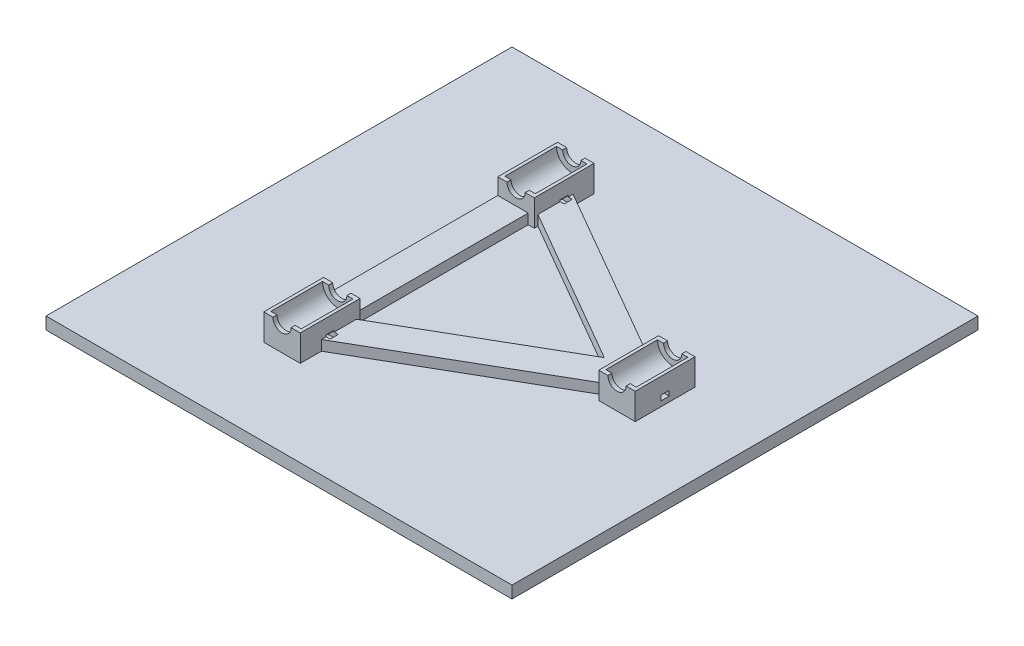
SolidWorks part; units mm, degrees
ref_plane "Front Plane" through (0, 0, 0) normal (0, 0, 1) x (1, 0, 0)
ref_plane "Top Plane" through (0, 0, 0) normal (0, 1, 0) x (1, 0, 0)
ref_plane "Right Plane" through (0, 0, 0) normal (1, 0, 0) x (0, 0, -1)
sketch "bottom" plane through (0, 0, 0) normal (0, 1, 0) x (1, 0, 0)
  line L0 (-133.0584, -12.7792) -> (96.9416, -12.7792) construction
  line L1 (-133.0584, 102.2208) -> (96.9416, 102.2208)
  line L2 (-133.0584, 102.2208) -> (-133.0584, -127.7792)
  line L3 (-133.0584, -127.7792) -> (96.9416, -127.7792)
  line L4 (96.9416, 102.2208) -> (96.9416, -127.7792)
  line L5 (-18.0584, 102.2208) -> (-18.0584, -127.7792) construction
  dimension "D1" = 230
  dimension "D2" = 230
extrude "Boss-Extrude2" add sketch "bottom" along normal blind 6
sketch "Sketch4" plane through (0, 6, 0) normal (0, 1, 0) x (1, 0, 0)
  line L0 (-133.0584, -12.7792) -> (96.9416, -12.7792) construction
  line L1 (-133.0584, 102.2208) -> (-133.0584, -127.7792) construction
  line L2 (96.9416, -127.7792) -> (96.9416, 102.2208) construction
  line L3 (-68.0584, 59.7208) -> (-68.0584, -85.2792)
  line L4 (96.9416, 102.2208) -> (-133.0584, 102.2208) construction
  line L5 (-18.0584, 102.2208) -> (-18.0584, -127.7792) construction
  line L6 (-133.0584, -127.7792) -> (96.9416, -127.7792) construction
  line L7 (-68.0584, -85.2792) -> (57.5153, -12.7792)
  line L8 (57.5153, -12.7792) -> (-68.0584, 59.7208)
  line L9 (-68.0584, -12.7792) -> (57.5153, -12.7792) construction
  line L10 (-53.0584, -59.2984) -> (-53.0584, 33.7401)
  line L11 (-53.0584, 33.7401) -> (27.5153, -12.7792)
  line L12 (57.5153, -12.7792) -> (-68.0584, -12.7792) construction
  line L13 (27.5153, -12.7792) -> (-53.0584, -59.2984)
  dimension "D1" = 145
  dimension "D2" = 145
  dimension "D3" = 50
  dimension "D4" = 15
  dimension "D5" = 15
extrude "Triangle" add sketch "Sketch4" along normal blind 5
sketch "Sketch5" plane through (0, 11, 0) normal (0, 1, 0) x (1, 0, 0)
  line L0 (39.5153, -12.7792) -> (57.5153, -12.7792) construction
  line L1 (-68.0584, 59.7208) -> (-50.0584, 59.7208)
  line L2 (-68.0584, 59.7208) -> (-68.0584, 30.2208)
  line L3 (-68.0584, 30.2208) -> (-50.0584, 30.2208)
  line L4 (-50.0584, 59.7208) -> (-50.0584, 30.2208)
  line L5 (-68.0584, -85.2792) -> (-50.0584, -85.2792)
  line L6 (-68.0584, -85.2792) -> (-68.0584, -55.7792)
  line L7 (-68.0584, -55.7792) -> (-50.0584, -55.7792)
  line L8 (-50.0584, -85.2792) -> (-50.0584, -55.7792)
  line L9 (39.5153, 1.9708) -> (57.5153, 1.9708)
  line L10 (39.5153, 1.9708) -> (39.5153, -27.5292)
  line L11 (39.5153, -27.5292) -> (57.5153, -27.5292)
  line L12 (57.5153, 1.9708) -> (57.5153, -27.5292)
  line L14 (48.5153, 1.9708) -> (48.5153, -27.5292) construction
  dimension "D1" = 29.5
  dimension "D2" = 18
extrude "Boss-Extrude4" add sketch "Sketch5" along normal blind 8 and the other way blind 6
sketch "Sketch6" plane through (0, 0, -30.2208) normal (0, 0, 1) x (1, 0, 0)
  line L0 (-68.0584, 19) -> (-50.0584, 19) construction
  circle A0 centre (-59.0584, 19) radius 4.5
  dimension "D1" = 9
extrude "Rod cutout" cut sketch "Sketch6" against normal up to surface and the other way up to surface up to face at (-59.0584, 12.5, -59.7208) other way up to face at (-59.0584, 12.5, 85.2792)
sketch "Sketch7" plane through (0, 0, -30.2208) normal (0, 0, 1) x (1, 0, 0)
  circle A0 centre (-59.0584, 19) radius 7.5
  dimension "D1" = 15
extrude "LM8Socket 1" cut sketch "Sketch7" against normal blind 25.5 from offset 2 offset against normal yes
sketch "Sketch8" plane through (0, 0, 55.7792) normal (0, 0, -1) x (-1, 0, 0)
  circle A0 centre (59.0584, 19) radius 7.5
  dimension "D1" = 15
extrude "LM8Socket 2" cut sketch "Sketch8" against normal blind 25.5 from offset 2 offset against normal yes
sketch "Sketch9" plane through (0, 0, -1.9708) normal (0, 0, -1) x (-1, 0, 0)
  line L0 (-57.5153, 19) -> (-39.5153, 19) construction
  circle A0 centre (-48.5153, 19) radius 4.5
  dimension "D1" = 9
extrude "Cut-Extrude4" cut sketch "Sketch9" against normal up to surface (29.5 mm away) up to face at (48.5153, 12.5, 27.5292)
sketch "Sketch11" plane through (0, 0, -1.9708) normal (0, 0, -1) x (-1, 0, 0)
  circle A0 centre (-48.5153, 19) radius 7.5
  dimension "D1" = 15
extrude "Cut-Extrude5" cut sketch "Sketch11" against normal blind 25.5 from offset 2 offset against normal yes
sketch "Sketch12" plane through (-68.0584, 0, 0) normal (-1, 0, 0) x (0, 0, 1)
  line L0 (-44.9708, 11) -> (-44.9708, 8.5) construction
  line L1 (-46.9708, 11) -> (-42.9708, 11)
  line L2 (-46.9708, 11) -> (-46.9708, 8.5)
  line L3 (-46.9708, 8.5) -> (-42.9708, 8.5)
  line L4 (-42.9708, 11) -> (-42.9708, 8.5)
  line L6 (-30.2208, 11) -> (55.7792, 11) construction
  line L7 (-44.9708, 19) -> (-44.9708, 6) construction
  line L8 (-59.7208, 19) -> (-30.2208, 19) construction
  line L9 (-59.7208, 6) -> (85.2792, 6) construction
  line L10 (12.7792, 6) -> (12.7792, 11) construction
  line L11 (72.5292, 8.5) -> (68.5292, 8.5)
  line L12 (68.5292, 11) -> (68.5292, 8.5)
  line L13 (72.5292, 11) -> (68.5292, 11)
  line L14 (72.5292, 11) -> (72.5292, 8.5)
  dimension "D1" = 4
  dimension "D2" = 2.5
extrude "Cut-Extrude8" cut sketch "Sketch12" against normal blind 20
fillet "Fillet1" radius 1 1 edges at (-50.0584, 11, -44.9708)
fillet "Fillet2" radius 1 1 edges at (-50.0584, 11, 70.5292)
sketch "Sketch13" plane through (57.5153, 0, 0) normal (1, 0, 0) x (0, 0, -1)
  line L1 (-14.7792, 11) -> (-10.7792, 11)
  line L2 (-14.7792, 11) -> (-14.7792, 8.5)
  line L3 (-14.7792, 8.5) -> (-10.7792, 8.5)
  line L4 (-10.7792, 11) -> (-10.7792, 8.5)
  line L5 (-12.7792, 11) -> (-12.7792, 8.5) construction
  line L7 (-27.5292, 6) -> (1.9708, 6) construction
  dimension "D1" = 4
  dimension "D2" = 2.5
  dimension "D3" = 5
extrude "Cut-Extrude9" cut sketch "Sketch13" against normal blind 20
